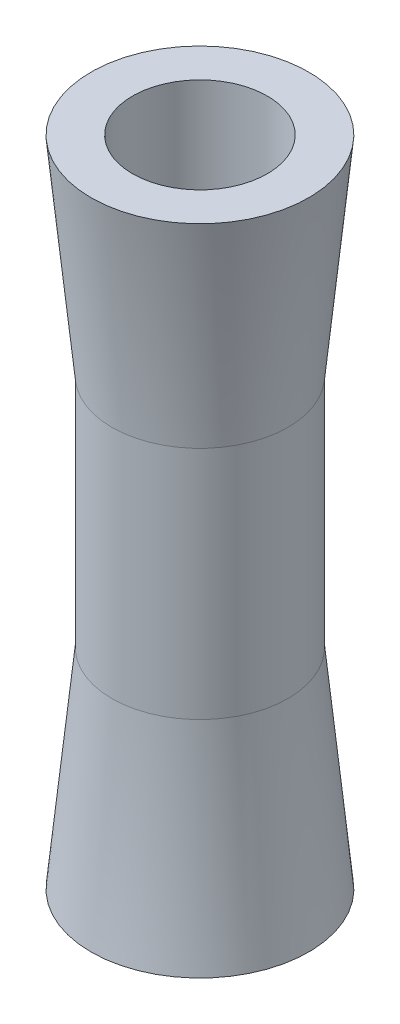
SolidWorks part; units mm, degrees
ref_plane "Front Plane" through (0, 0, 0) normal (0, 0, 1) x (1, 0, 0)
ref_plane "Top Plane" through (0, 0, 0) normal (0, 1, 0) x (1, 0, 0)
ref_plane "Right Plane" through (0, 0, 0) normal (1, 0, 0) x (0, 0, -1)
sketch "Sketch1" plane through (0, 0, 0) normal (0, 1, 0) x (1, 0, 0)
  circle A0 centre (0, 0) radius 6.5
  circle A1 centre (0, 0) radius 8.5
  dimension "D1" = 13
  dimension "D2" = 17
extrude "Boss-Extrude1" add sketch "Sketch1" along normal blind 63
sketch "Sketch2" plane through (0, 0, 0) normal (0, 0, 1) x (1, 0, 0)
  line L0 (6.5, 63) -> (6.5, 0)
  line L1 (6.5, 0) -> (10.5, 0)
  line L2 (6.5, 63) -> (10.5, 63)
  line L6 (0, -9.35) -> (0, 9.35) construction
  line L7 (-8.5, 0) -> (8.5, 0) construction
  arc A0 (10.5, 0) -> (10.5, 63) centre (225.4944, 31.5) cw
  dimension "D1" = 6.5
  dimension "D2" = 4
  dimension "D3" = 63
ref_axis "Axis1" through (0, 65.415, 0) along (0, -1, 0)
revolve "Revolve1" add sketch "Sketch2" angle 360 about axis through (0, 65.415, 0) along (0, -1, 0)
